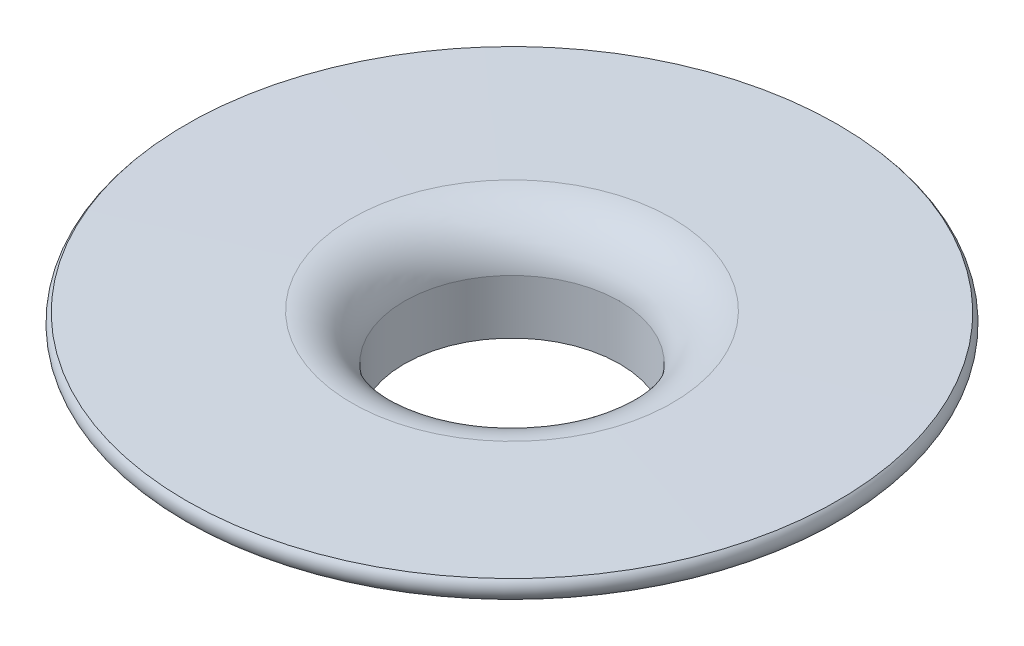
SolidWorks part; units mm, degrees
ref_plane "Front Plane" through (0, 0, 0) normal (0, 0, 1) x (1, 0, 0)
ref_plane "Top Plane" through (0, 0, 0) normal (0, 1, 0) x (1, 0, 0)
ref_plane "Right Plane" through (0, 0, 0) normal (1, 0, 0) x (0, 0, -1)
sketch "Sketch1" plane through (0, 0, 0) normal (1, 0, 0) x (0, 0, -1)
  line L0 (0, -237.6777) -> (0, 11646.2067) construction
  line L9 (-18, -1.25) -> (-8.75, -1.25)
  line L14 (-6.9484, -2.6795) -> (-6.9484, -5.6795)
  line L15 (-6.9484, -5.6795) -> (-5.9493, -5.6795)
  line L16 (-5.9493, -5.6795) -> (-5.9493, -2.6795)
  line L17 (-8.8474, -0.1572) -> (-18, -0.25)
  arc A2 (-18, -1.25) -> (-18, -0.25) centre (-17.5, -0.75) cw
  arc A3 (-8.75, -1.25) -> (-6.9484, -2.6795) centre (-8.75, -3.1) cw
  arc A4 (-5.9493, -2.6795) -> (-8.8474, -0.1572) centre (-8.9111, -3.1566) ccw
  dimension "D8" = 0.7071
  dimension "D2" = 1.85
  dimension "D4" = 3
  dimension "D1" = 1
  dimension "D3" = 36
  dimension "D7" = 9.25
  dimension "D10" = 3
  dimension "D11" = 3
revolve "Revolve1" add sketch "Sketch1" angle 360 about L0
